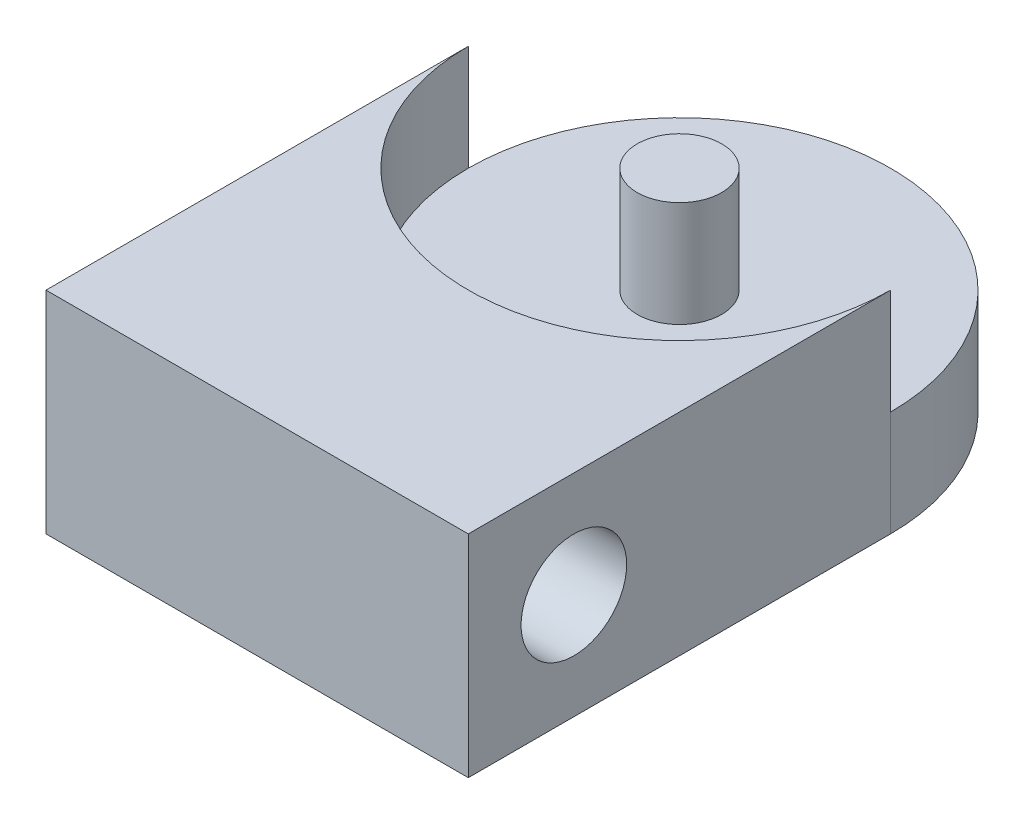
SolidWorks part; units mm, degrees
ref_plane "Ebene vorne" through (0, 0, 0) normal (0, 0, 1) x (1, 0, 0)
ref_plane "Ebene oben" through (0, 0, 0) normal (0, 1, 0) x (1, 0, 0)
ref_plane "Ebene rechts" through (0, 0, 0) normal (1, 0, 0) x (0, 0, -1)
sketch "Skizze1" plane through (0, 0, 0) normal (0, 1, 0) x (1, 0, 0)
  line L0 (-10, 0) -> (-10, -20)
  line L1 (-10, -20) -> (10, -20)
  line L2 (10, -20) -> (10, 0)
  line L3 (10, 0) -> (-10, 0)
  circle A1 centre (0, 0) radius 10
  dimension "D1" = 20
  dimension "D2" = 20
extrude "Aufsatz-Linear austragen1" add sketch "Skizze1" along normal blind 5 contours L3 A1 | L3 A1 | A1 L0 L1 L2
sketch "Skizze2" plane through (0, 5, 0) normal (0, 1, 0) x (1, 0, 0)
  line L3 (10, -20) -> (10, 0)
  line L4 (-10, 0) -> (-10, -20)
  line L5 (-10, -20) -> (10, -20)
  line L6 (10, -20) -> (10, 0)
  line L7 (-10, 0) -> (-10, -20)
  line L8 (-10, -20) -> (10, -20)
  circle A0 centre (0, 0) radius 2
  circle A1 centre (0, 0) radius 10
  arc A2 (10, 0) -> (-10, 0) centre (0, 0) ccw
  arc A3 (10, 0) -> (-10, 0) centre (0, 0) ccw
  line M5 (10, -20) -> (10, 0)
  line M7 (-10, 0) -> (-10, -20)
  line M8 (-10, -20) -> (10, -20)
  dimension "D1" = 4
  dimension "D2" = 0
extrude "Aufsatz-Linear austragen2" add sketch "Skizze2" along normal blind 5 contours A0 | A1 M7 M8 M5
sketch "Skizze3" plane through (10, 0, 0) normal (1, 0, 0) x (0, 0, -1)
  line L0 (0, 5) -> (-10, 5) construction
  line L1 (0, 5.5) -> (0, -5.5) construction
  line L2 (10, 5) -> (0, 5) construction
  line L3 (-20, 5) -> (-10, 5) construction
  line L4 (-20, 10) -> (-20, 0) construction
  circle A0 centre (-15, 5) radius 2.5
  dimension "D2" = 5
  dimension "D1" = 10
extrude "Schnitt-Linear austragen1" cut sketch "Skizze3" against normal through all
